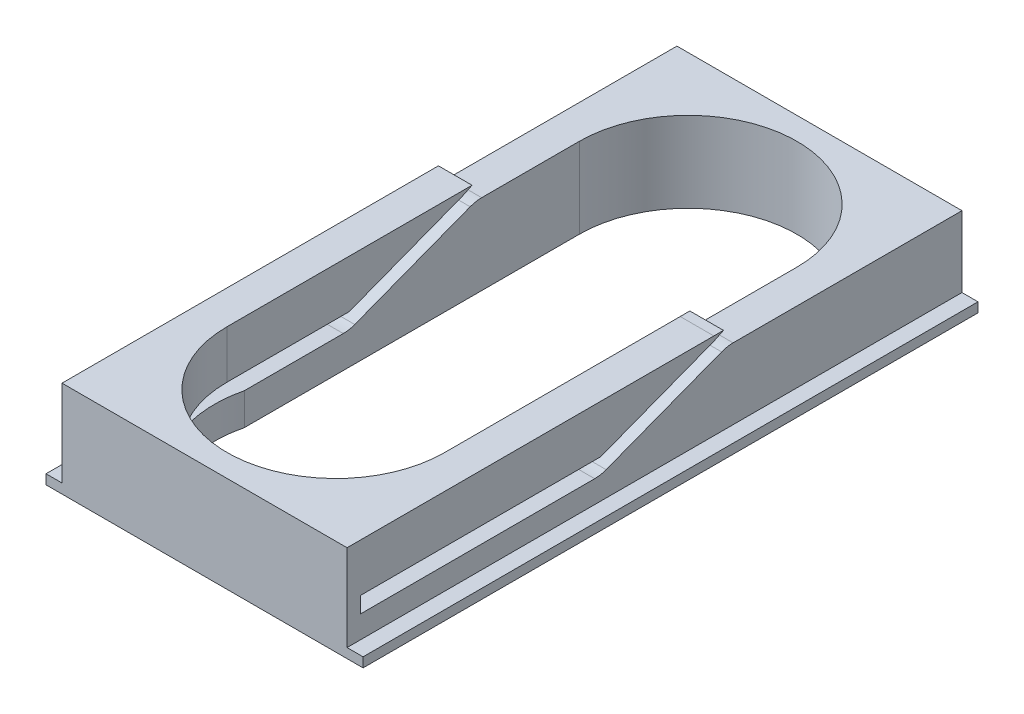
SolidWorks part; units mm, degrees
ref_plane "Front Plane" through (0, 0, 0) normal (0, 0, 1) x (1, 0, 0)
ref_plane "Top Plane" through (0, 0, 0) normal (0, 1, 0) x (1, 0, 0)
ref_plane "Right Plane" through (0, 0, 0) normal (1, 0, 0) x (0, 0, -1)
sketch "Sketch1" plane through (0, 0, 0) normal (0, 1, 0) x (1, 0, 0)
  line L0 (-10.5, -34.9563) -> (-10.5, 75.0437) construction
  line L1 (-55, -75.9563) -> (34, -75.9563)
  line L2 (-55, -75.9563) -> (-55, 116.0437)
  line L3 (-55, 116.0437) -> (34, 116.0437)
  line L4 (34, -75.9563) -> (34, 116.0437)
  line L5 (-44.5, -34.9563) -> (-44.5, 75.0437)
  line L6 (23.5, -34.9563) -> (23.5, 75.0437)
  arc A0 (-44.5, -34.9563) -> (23.5, -34.9563) centre (-10.5, -34.9563) ccw
  arc A1 (23.5, 75.0437) -> (-44.5, 75.0437) centre (-10.5, 75.0437) ccw
  point P6 (-10.5, 20.0437)
  dimension "D3" = 10.5
  dimension "D4" = 41
  dimension "D1" = 34
  dimension "D2" = 41
  dimension "D6" = 10.5
extrude "Boss-Extrude1" add sketch "Sketch1" along normal blind 30
sketch "Sketch2" plane through (0, 0, 0) normal (0, -1, 0) x (1, 0, 0)
  circle A0 centre (-10.5, 37.8388) radius 34.9994
extrude "Cut-Extrude1" cut sketch "Sketch2" against normal blind 10
sketch "Sketch3" plane through (34, 0, 0) normal (1, 0, 0) x (0, 0, -1)
  line L0 (-75.9563, 0) -> (116.0437, 0) construction
  line L1 (-71.7863, 10) -> (3.2137, 10)
  line L2 (-71.7863, 10) -> (-71.7863, 15)
  line L3 (-71.7863, 15) -> (3.2137, 15)
  line L4 (3.2137, 10) -> (3.2137, 15)
  dimension "D1" = 5
  dimension "D2" = 10
  dimension "D3" = 75
extrude "Cut-Extrude2" cut sketch "Sketch3" against normal blind 102
sketch "Sketch4" plane through (-55, 0, 0) normal (-1, 0, 0) x (0, 0, 1)
  line L1 (-40.9707, 29.4694) -> (-41.2116, 24.5617)
  line L4 (-40.9707, 29.4694) -> (-3.2137, 15)
  line L5 (-3.2137, 15) -> (-3.2137, 10)
  line L6 (-3.2137, 10) -> (-41.2116, 24.5617)
extrude "Cut-Extrude4" cut sketch "Sketch4" against normal blind 102
sketch "Sketch6" plane through (0, 30, 0) normal (0, 1, 0) x (1, 0, 0)
  line L0 (-44.5, 75.0437) -> (-44.5, -34.9563) construction
  line L1 (-55, 42.5706) -> (-44.5, 42.5706)
  line L2 (-55, 42.5706) -> (-55, 38.5706)
  line L3 (-55, 38.5706) -> (-44.5, 38.5706)
  line L4 (-44.5, 42.5706) -> (-44.5, 38.5706)
  line L7 (23.5, 42.5706) -> (23.5, 38.5706)
  line L8 (34, 38.5706) -> (23.5, 38.5706)
  line L9 (34, 42.5706) -> (34, 38.5706)
  line L10 (34, 42.5706) -> (23.5, 42.5706)
  dimension "D1" = 4
extrude "Cut-Extrude7" cut sketch "Sketch6" against normal blind 8
sketch "Sketch7" plane through (-55, 0, 0) normal (-1, 0, 0) x (0, 0, 1)
  line L0 (-38.5706, 23.5496) -> (-42.5706, 25.0825)
  line L1 (-42.5706, 22) -> (-42.5706, 30) construction
  line L2 (-42.5706, 25.0825) -> (-42.5706, 22)
  line L3 (-42.5706, 22) -> (-38.5706, 22)
  line L4 (-38.5706, 22) -> (-38.5706, 23.5496)
extrude "Boss-Extrude2" add sketch "Sketch7" against normal up to surface (10.5 mm away) up to face at (-44.5, 16.3944, -28.5016)
sketch "Sketch8" plane through (-55, 0, 0) normal (-1, 0, 0) x (0, 0, 1)
  line L0 (-42.5706, 25.0825) -> (-55.4025, 30)
  line L1 (-116.0437, 30) -> (-42.5706, 30) construction
  line L2 (-55.4025, 30) -> (-42.5706, 30)
  line L3 (-42.5706, 30) -> (-42.5706, 25.0825)
extrude "Cut-Extrude8" cut sketch "Sketch8" against normal blind 20.7678
sketch "Sketch9" plane through (34, 0, 0) normal (1, 0, 0) x (0, 0, -1)
  line L0 (38.5706, 23.5496) -> (42.5706, 25.0825)
  line L1 (42.5706, 22) -> (42.5706, 30) construction
  line L2 (42.5706, 25.0825) -> (42.5706, 22)
  line L3 (42.5706, 22) -> (38.5706, 22)
  line L4 (38.5706, 22) -> (38.5706, 23.5496)
extrude "Boss-Extrude3" add sketch "Sketch9" against normal up to surface (10.5 mm away) up to face at (23.5, 16.3944, -28.5016)
sketch "Sketch10" plane through (34, 0, 0) normal (1, 0, 0) x (0, 0, -1)
  line L0 (42.5706, 25.0825) -> (55.4025, 30)
  line L1 (42.5706, 30) -> (116.0437, 30) construction
  line L2 (55.4025, 30) -> (42.5706, 30)
  line L3 (42.5706, 30) -> (42.5706, 25.0825)
extrude "Cut-Extrude9" cut sketch "Sketch10" against normal blind 22.8125
sketch "Sketch11" plane through (34, 0, 0) normal (1, 0, 0) x (0, 0, -1)
  line L0 (38.5706, 28.5496) -> (41.5706, 30.0071)
  line L1 (41.5706, 30.0071) -> (38.5706, 30)
  line L4 (38.5706, 30) -> (38.5706, 28.5496)
  point P3 (55.4025, 30)
  dimension "D1" = 3
sketch "Sketch12" plane through (-55, 0, 0) normal (-1, 0, 0) x (0, 0, 1)
  line L0 (-38.5706, 30) -> (-41.5706, 30)
  line L1 (-41.5706, 30) -> (-38.5706, 28.5496)
  line L2 (-38.5706, 28.5496) -> (-38.5706, 30)
  point P3 (-55.4025, 30)
  dimension "D1" = 3
extrude "Boss-Extrude6" add sketch "Sketch12" against normal up to surface (10.5 mm away) up to face at (-44.5, 23.7099, -2.0885)
extrude "Boss-Extrude7" add sketch "Sketch11" against normal up to surface (10.5 mm away) up to face at (23.5, 23.7099, -2.0885)
fillet "Fillet1" radius 10 1 edges at (-49.75, 30, -55.4025)
fillet "Fillet2" radius 10 1 edges at (28.75, 30, -55.4025)
fillet "Fillet3" radius 10 1 edges at (-49.75, 10, -3.2137)
fillet "Fillet4" radius 10 1 edges at (28.75, 10, -3.2137)
sketch "Sketch14" plane through (34, 0, 0) normal (1, 0, 0) x (0, 0, -1)
  line L0 (42.7174, 25.1388) -> (116.0437, 25.1388)
  line L1 (53.6745, 29.3378) -> (4.9417, 10.6622) construction
  line L2 (116.0437, 30) -> (116.0437, 0) construction
  line L3 (42.7174, 25.1388) -> (53.6745, 29.3378)
  line L4 (53.6745, 29.3378) -> (57.253, 30)
  line L5 (57.253, 30) -> (116.0437, 30)
  line L6 (116.0437, 30) -> (116.0437, 25.1388)
extrude "Cut-Extrude11" cut sketch "Sketch14" against normal blind 99
sketch "Sketch15" plane through (34, 0, 0) normal (1, 0, 0) x (0, 0, -1)
  line L1 (51.0699, 31.494) -> (58.6241, 31.494)
  line L2 (51.0699, 31.494) -> (51.0699, 28.2348)
  line L3 (51.0699, 28.2348) -> (58.6241, 28.2348)
  line L4 (58.6241, 31.494) -> (58.6241, 28.2348)
extrude "Cut-Extrude12" cut sketch "Sketch15" against normal blind 99
fillet "Fillet5" radius 10 2 edges at (-49.75, 25.1388, -42.7174) (28.75, 25.1388, -42.7174)
sketch "Sketch16" plane through (0, 0, 0) normal (1, 0, 0) x (0, 0, -1)
  line L0 (44.5679, 25.1388) -> (116.0437, 25.1388) construction
  line L1 (116.0437, 15.1388) -> (120.9375, 15.1388)
  line L2 (116.0437, 15.1388) -> (116.0437, 7.1388)
  line L3 (116.0437, 7.1388) -> (120.9375, 7.1388)
  line L4 (120.9375, 15.1388) -> (120.9375, 7.1388)
  line L5 (116.0437, 25.1388) -> (116.0437, 0) construction
  dimension "D1" = 10
  dimension "D2" = 8
  dimension "D3" = 0
extrude "Boss-Extrude8" add sketch "Sketch16" along normal blind 4
sketch "Sketch17" plane through (4, 0, 0) normal (1, 0, 0) x (0, 0, -1)
  circle A0 centre (117.8934, 11.1388) radius 2
extrude "Cut-Extrude13" cut sketch "Sketch17" against normal blind 4
sketch "Sketch18" plane through (34, 0, 0) normal (1, 0, 0) x (0, 0, -1)
  line L0 (116.0437, 25.1388) -> (116.0437, 0) construction
  line L1 (-75.9563, 0) -> (116.0437, 0)
  line L2 (-75.9563, 0) -> (-75.9563, 3)
  line L3 (-75.9563, 3) -> (116.0437, 3)
  line L4 (116.0437, 0) -> (116.0437, 3)
  dimension "D1" = 3
extrude "Boss-Extrude9" add sketch "Sketch18" along normal blind 5
sketch "Sketch19" plane through (-55, 0, 0) normal (-1, 0, 0) x (0, 0, 1)
  line L0 (-116.0437, 25.1388) -> (-116.0437, 0) construction
  line L1 (75.9563, 0) -> (-116.0437, 0)
  line L2 (75.9563, 0) -> (75.9563, 3)
  line L3 (75.9563, 3) -> (-116.0437, 3)
  line L4 (-116.0437, 0) -> (-116.0437, 3)
  dimension "D1" = 3
extrude "Boss-Extrude10" add sketch "Sketch19" along normal blind 5
